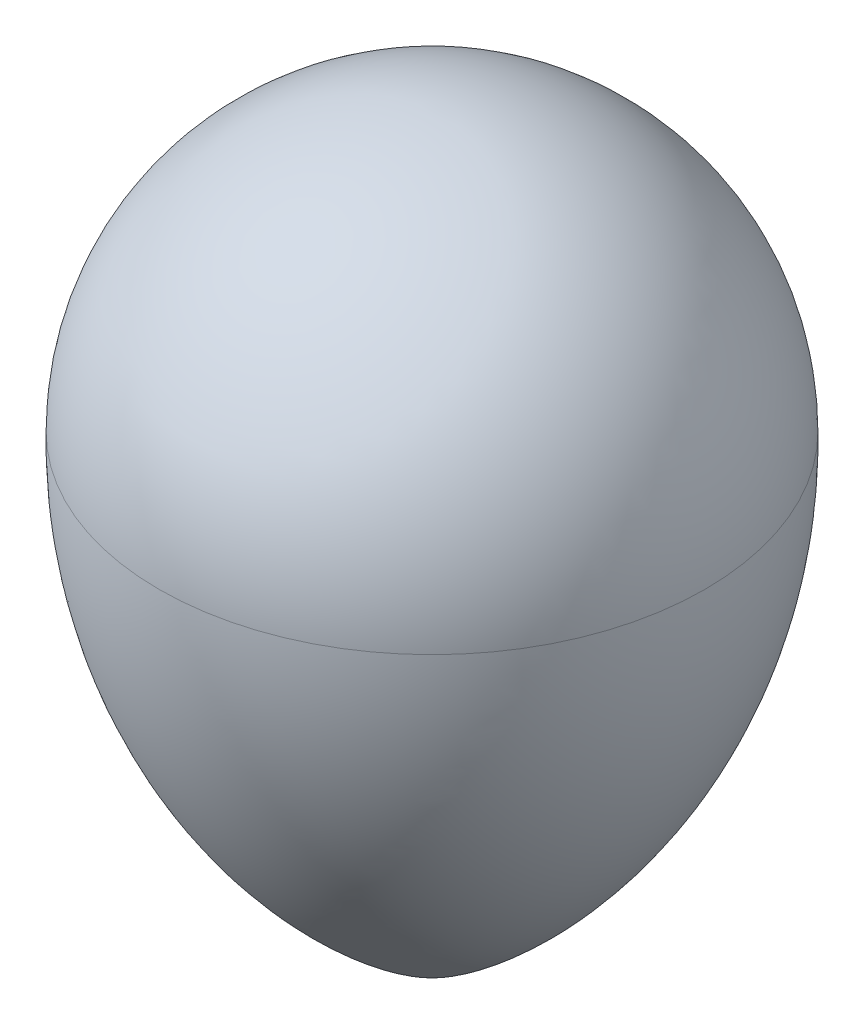
SolidWorks part; units mm, degrees
ref_plane "Front Plane" through (0, 0, 0) normal (0, 0, 1) x (1, 0, 0)
ref_plane "Top Plane" through (0, 0, 0) normal (0, 1, 0) x (1, 0, 0)
ref_plane "Right Plane" through (0, 0, 0) normal (1, 0, 0) x (0, 0, -1)
sketch "Sketch2" plane through (0, 0, 0) normal (0, 0, 1) x (1, 0, 0)
  line L0 (0, 93.4528) -> (0, -160.5472)
  line L1 (0, 158.4711) -> (0, -218.773) construction
  arc A0 (0, 93.4528) -> (93.4528, 0) centre (0, 0) cw
  arc A1 (93.4528, 0) -> (0, -160.5472) centre (-86.7541, -2.576) cw
  dimension "D1" = 254
revolve "Revolve1" add sketch "Sketch2" angle 360 about L0
sketch "Sketch3" plane through (0, 0, 0) normal (0, 0, 1) x (1, 0, 0)
  line L0 (0, -236.0154) -> (0, 161.0836) construction
  line L1 (-93.4528, 0) -> (93.4528, 0)
  line L2 (93.4528, 0) -> (-93.4528, 0) construction
  arc A0 (93.4528, 0) -> (-93.4528, 0) centre (0, 0) ccw construction
  point P3 (0, 0)
